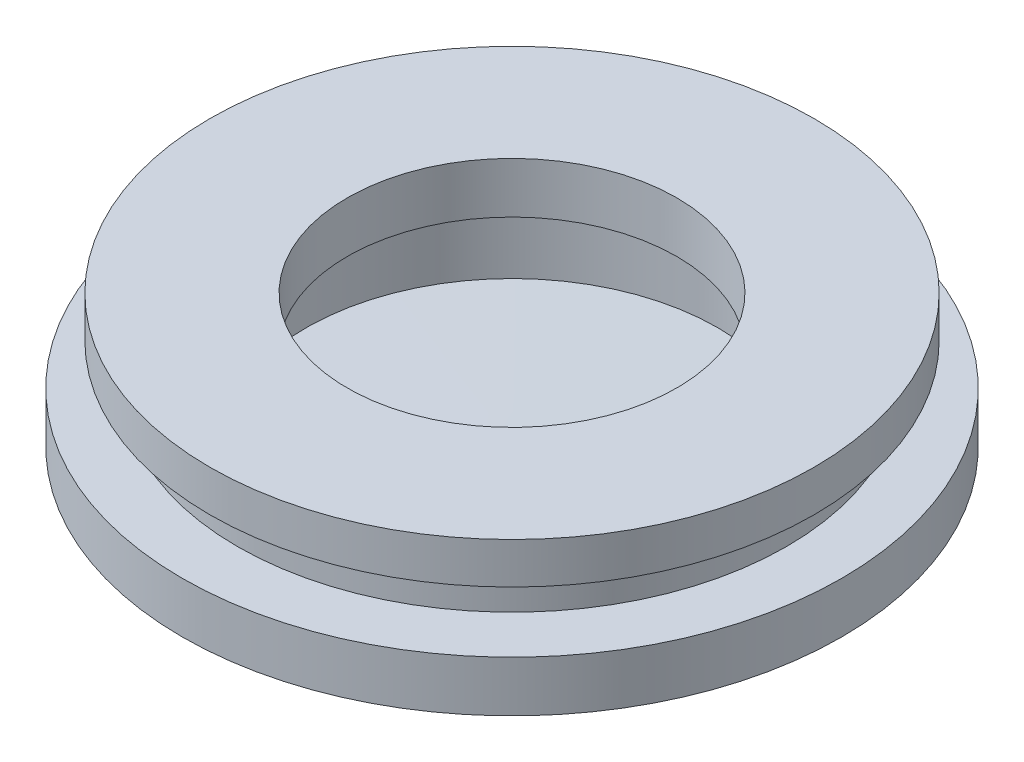
SolidWorks part; units mm, degrees
ref_plane "Front Plane" through (0, 0, 0) normal (0, 0, 1) x (1, 0, 0)
ref_plane "Top Plane" through (0, 0, 0) normal (0, 1, 0) x (1, 0, 0)
ref_plane "Right Plane" through (0, 0, 0) normal (1, 0, 0) x (0, 0, -1)
sketch "Sketch2" plane through (0, 0, 0) normal (0, 0, 1) x (1, 0, 0)
  line L0 (0, 0) -> (0, 9.2201)
  line L1 (0, 9.2201) -> (-11, 9.2201)
  line L2 (-11, 9.2201) -> (-11, 7.7201)
  line L3 (-11, 7.7201) -> (-10, 7.7201)
  line L4 (-10, 7.7201) -> (-10, 6.2201)
  line L5 (-10, 6.2201) -> (-12.0068, 6.2201)
  line L6 (-12.0068, 6.2201) -> (-12.0068, 4.3701)
  line L7 (-12.0068, 4.3701) -> (0, 0)
  point P3 (-10, 6.9701)
  dimension "D1" = 11
  dimension "D2" = 10
  dimension "D3" = 1.5
  dimension "D4" = 1.5
  dimension "D5" = 1.85
  dimension "D6" = 20
revolve "Revolve1" add sketch "Sketch2" angle 360 about L0
sketch "Sketch3" plane through (0, 0, 0) normal (0, 0, 1) x (1, 0, 0)
  line L0 (0, 0) -> (0, 12.7849) construction
  line L2 (0, 0) -> (-9.3315, 0) construction
  line L3 (0, 4.4411) -> (0, 10.3701)
  line L4 (0, 10.3701) -> (-6, 10.3701)
  line L5 (-6, 10.3701) -> (-6, 7.3701)
  line L6 (-6, 7.3701) -> (-7.5, 7.3701)
  line L7 (-7.5, 7.3701) -> (-7.5, 4.3701)
  line L8 (12.0068, 4.3701) -> (-12.0068, 4.3701) construction
  line L9 (-7.5, 4.3701) -> (0, 4.4411)
  dimension "D1" = 3
  dimension "D2" = 3
  dimension "D3" = 7.5
  dimension "D4" = 6
revolve "Cut-Revolve1" cut sketch "Sketch3" angle 360 about L3
